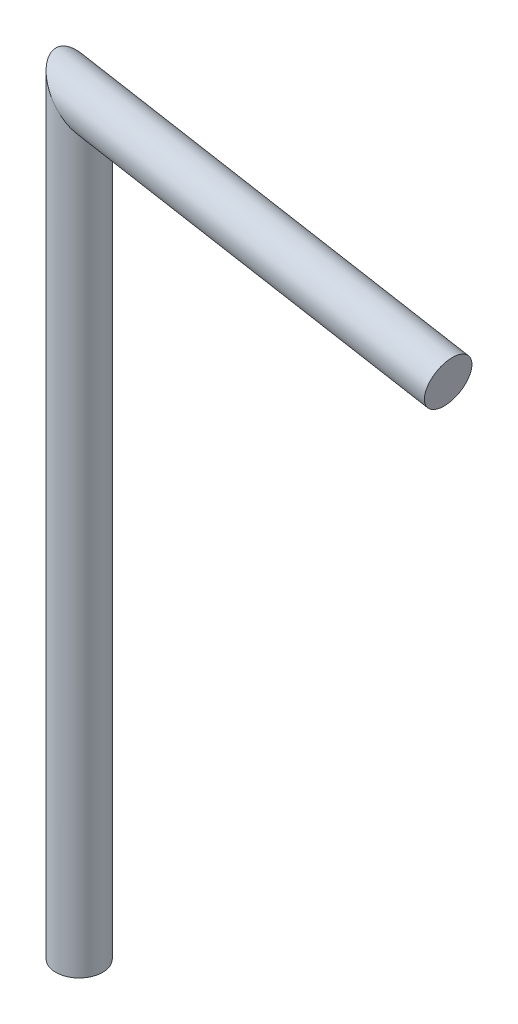
SolidWorks part; units mm, degrees
ref_plane "Front" through (0, 0, 0) normal (0, 0, 1) x (1, 0, 0)
ref_plane "Top" through (0, 0, 0) normal (0, 1, 0) x (1, 0, 0)
ref_plane "Right" through (0, 0, 0) normal (1, 0, 0) x (0, 0, -1)
sketch "草图5" plane through (0, 0, 0) normal (0, 1, 0) x (1, 0, 0)
  circle A0 centre (0, 0) radius 2.5
  dimension "D1" = 5
sketch "草图6" plane through (0, 0, 0) normal (0, 0, 1) x (1, 0, 0)
  line L0 (0, 0) -> (0, 80)
  line L1 (0, 80) -> (39.3923, 73.0541)
  dimension "D1" = 80
  dimension "D2" = 40
  dimension "D3" = 80
sweep "扫描1" add profiles "草图5" path "草图6"
